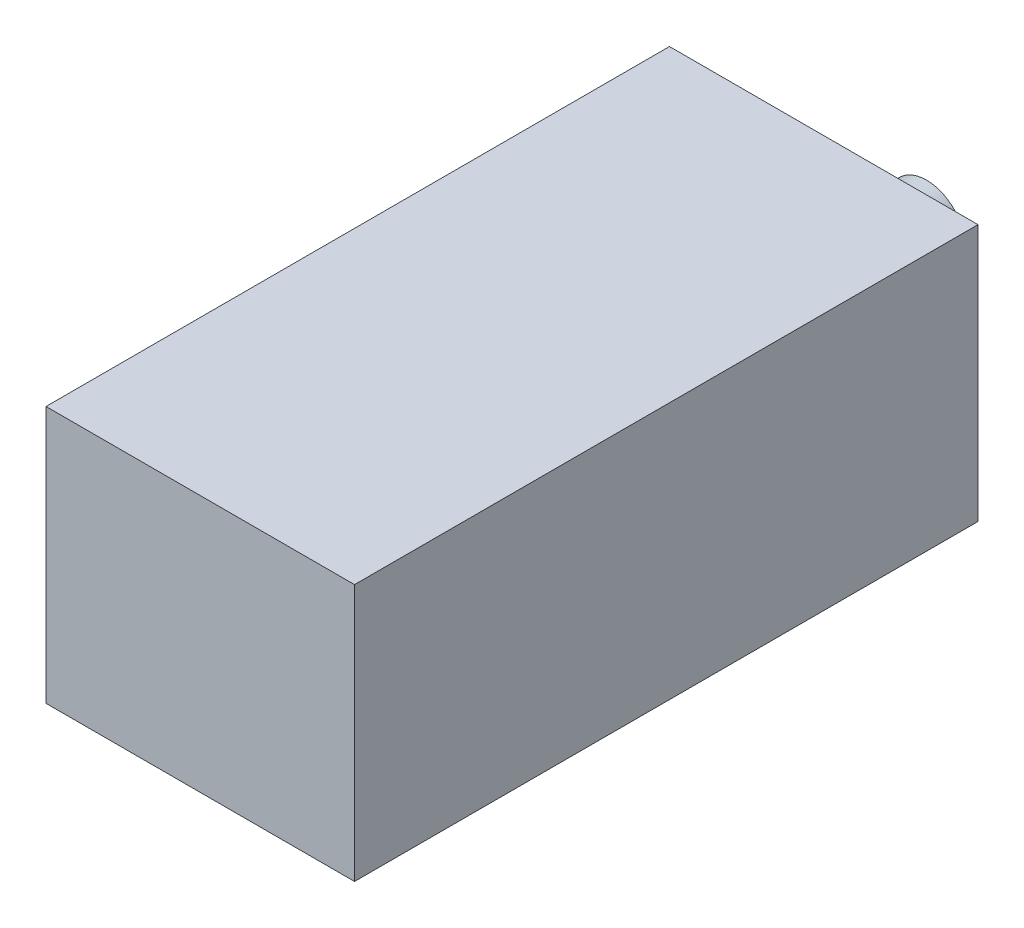
SolidWorks part; units mm, degrees
ref_plane "Front Plane" through (0, 0, 0) normal (0, 0, 1) x (1, 0, 0)
ref_plane "Top Plane" through (0, 0, 0) normal (0, 1, 0) x (1, 0, 0)
ref_plane "Right Plane" through (0, 0, 0) normal (1, 0, 0) x (0, 0, -1)
sketch "Sketch1" plane through (0, 0, 0) normal (0, 0, 1) x (1, 0, 0)
  line L1 (0, 0) -> (12, 0)
  line L2 (0, 0) -> (0, -10)
  line L3 (0, -10) -> (12, -10)
  line L4 (12, 0) -> (12, -10)
  dimension "D1" = 12
  dimension "D2" = 10
extrude "Boss-Extrude1" add sketch "Sketch1" along normal blind 24.25
sketch "Sketch2" plane through (0, 0, 0) normal (0, 0, -1) x (-1, 0, 0)
  line L1 (0, 0) -> (0, -10) construction
  line L3 (-12, 0) -> (0, 0) construction
  circle A0 centre (-10.5, -5) radius 0.5
  circle A1 centre (-1.5, -5) radius 0.5
  dimension "D1" = 1
  dimension "D2" = 1
  dimension "D3" = 9
  dimension "D4" = 1.5
  dimension "D5" = 5
  dimension "D6" = 0
extrude "Cut-Extrude1" cut sketch "Sketch2" against normal blind 10
sketch "Sketch3" plane through (0, 0, 0) normal (0, 0, -1) x (-1, 0, 0)
  line L0 (-12, -10) -> (-12, 0) construction
  line L1 (-12, 0) -> (0, 0) construction
  circle A0 centre (-6, -5) radius 1.5
  dimension "D3" = 3
  dimension "D1" = 6
  dimension "D2" = 5
extrude "Boss-Extrude2" add sketch "Sketch3" along normal blind 4
